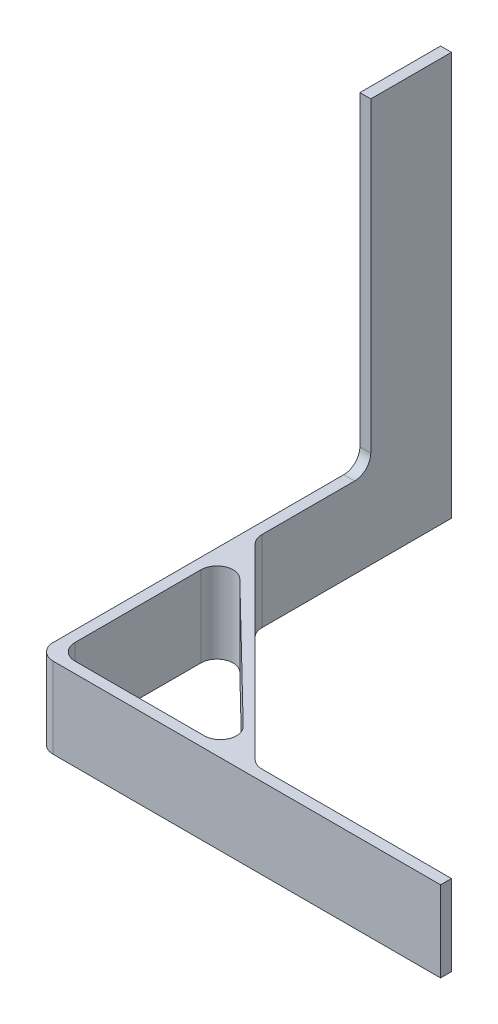
SolidWorks part; units mm, degrees
ref_plane "Front Plane" through (0, 0, 0) normal (0, 0, 1) x (1, 0, 0)
ref_plane "Top Plane" through (0, 0, 0) normal (0, 1, 0) x (1, 0, 0)
ref_plane "Right Plane" through (0, 0, 0) normal (1, 0, 0) x (0, 0, -1)
sketch "Sketch1" plane through (0, 0, 0) normal (0, 1, 0) x (1, 0, 0)
  line L1 (0, 0) -> (-250, 0)
  line L2 (0, 0) -> (0, 6.754)
  line L3 (0, 6.754) -> (-250, 6.754)
  line L4 (-250, 0) -> (-250, 6.754)
extrude "Boss-Extrude2" add sketch "Sketch1" along normal blind 50
sketch "Sketch2" plane through (0, 0, 0) normal (0, 1, 0) x (1, 0, 0)
  line L1 (-250, 0) -> (-243.25, 0)
  line L2 (-250, 0) -> (-250, 250)
  line L3 (-250, 250) -> (-243.25, 250)
  line L4 (-243.25, 0) -> (-243.25, 250)
extrude "Boss-Extrude3" add sketch "Sketch2" along normal blind 50
sketch "Sketch3" plane through (0, 0, 0) normal (0, 1, 0) x (1, 0, 0)
  line L0 (-243.25, 6.754) -> (-243.25, 250) construction
  line L1 (-243.25, 128.377) -> (-121.625, 6.754)
  line L2 (0, 6.754) -> (-243.25, 6.754) construction
  line L3 (-121.625, 6.754) -> (-121.625, 0)
  line L4 (-121.625, 0) -> (-250, 125)
  line L5 (-250, 250) -> (-250, 0) construction
  line L6 (-250, 125) -> (-243.25, 128.377)
  point P10 (0, 0)
extrude "Boss-Extrude4" add sketch "Sketch3" along normal blind 50
fillet "Fillet1" radius 10 1 edges at (-250, 25, 0)
fillet "Fillet2" radius 10 1 edges at (-243.25, 25, -6.754)
fillet "Fillet3" radius 10 1 edges at (-243.25, 25, -118.4275)
fillet "Fillet4" radius 10 1 edges at (-128.5613, 25, -6.754)
fillet "Fillet5" radius 10 1 edges at (-121.625, 25, -6.754)
fillet "Fillet6" radius 10 1 edges at (-243.25, 25, -128.377)
sketch "Sketch5" plane through (0, 0, 0) normal (0, 1, 0) x (1, 0, 0)
  line L0 (-243.25, 132.5192) -> (-243.25, 250) construction
  line L1 (-250, 250) -> (-243.25, 250)
  line L2 (-250, 250) -> (-250, 200)
  line L3 (-250, 200) -> (-243.25, 200)
  line L4 (-243.25, 250) -> (-243.25, 200)
extrude "Boss-Extrude5" add sketch "Sketch5" along normal blind 250
fillet "Fillet7" radius 10 1 edges at (-246.625, 50, -200)
